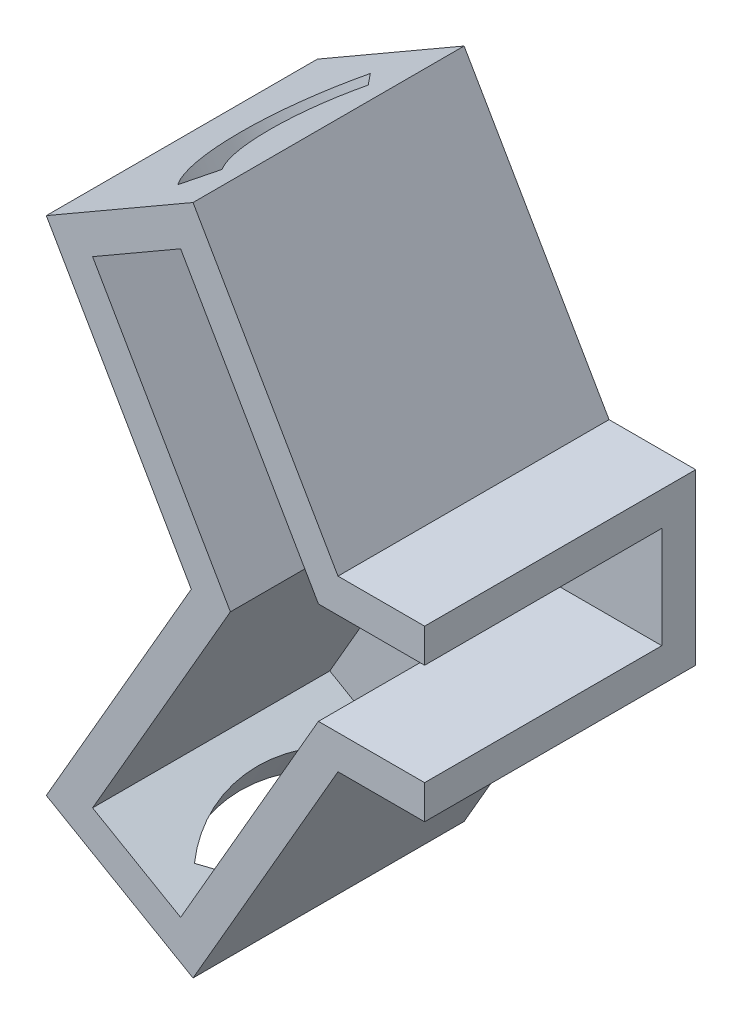
SolidWorks part; units mm, degrees
material "PET"
ref_plane "Front Plane" through (0, 0, 0) normal (1, 0, 0) x (0, 1, 0)
ref_plane "Top Plane" through (0, 0, 0) normal (0, 0, 1) x (0, 1, 0)
ref_plane "Right Plane" through (0, 0, 0) normal (0, 1, 0) x (-1, 0, 0)
sketch "Sketch1" plane through (0, 0, 0) normal (0, 0, 1) x (0, 1, 0)
  line L0 (0, 0) -> (0, 4)
  line L5 (0, 4) -> (8.6603, 9)
  dimension "D1" = 120
  dimension "D2" = 4
  dimension "D3" = 10
extrude "Extrude-Thin1" add sketch "Sketch1" along normal blind 8 thin thin type mid plane wall 5
mirror "Mirror3" about plane through (0, 0, 0) normal (0, 1, 0) of "Extrude-Thin1"
shell "Shell4" thickness 1
sketch "Sketch5" plane through (-6, 10.3923, 0) normal (-0.5, 0.866, 0) x (-0.866, -0.5, 0)
  line L2 (0.9641, 8) -> (0.9641, 0) construction
  line L3 (5.9641, 8) -> (0.9641, 8) construction
  arc A0 (2.4641, 6.5) -> (2.4641, 1.5) centre (-0.1609, 4) cw
  point P10 (0.9641, 4)
  point P11 (3.4641, 8)
  point P13 (3.4641, 4)
  dimension "D1" = 1
  dimension "D2" = 5
extrude "Cut-Extrude-Thin1" cut sketch "Sketch5" against normal blind 8 thin thin type mid plane wall 1
mirror "Mirror4" about plane through (0, 0, 0) normal (0, 1, 0) of "Cut-Extrude-Thin1"
